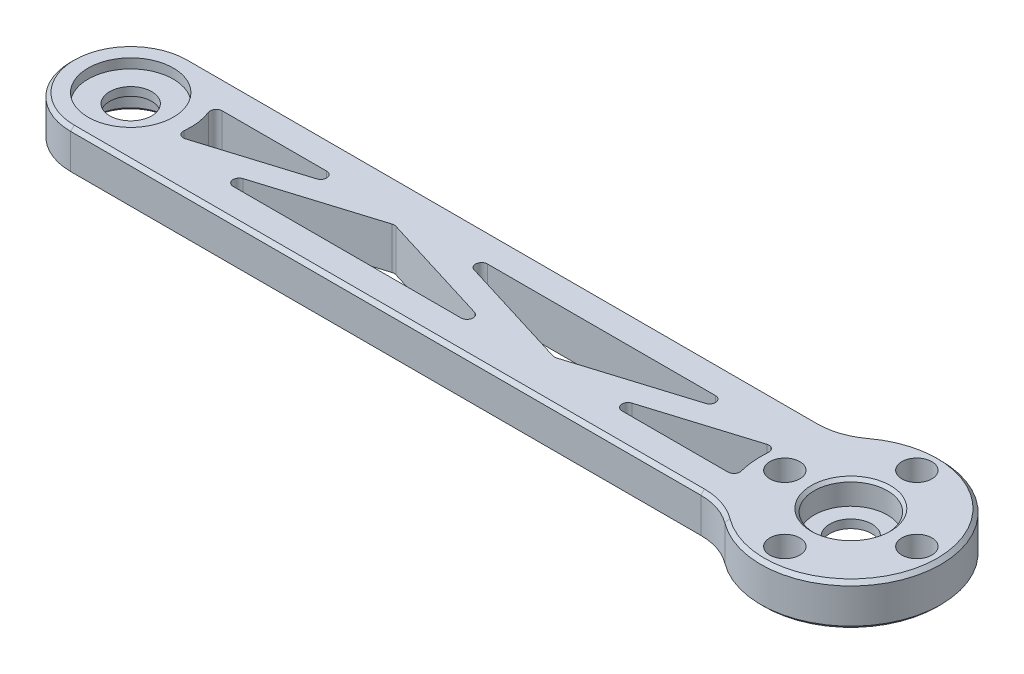
SolidWorks part; units mm, degrees
material "三聚氰胺甲醛树脂"
ref_plane "前视基准面" through (0, 0, 0) normal (0, 0, 1) x (1, 0, 0)
ref_plane "上视基准面" through (0, 0, 0) normal (0, 1, 0) x (1, 0, 0)
ref_plane "右视基准面" through (0, 0, 0) normal (1, 0, 0) x (0, 0, -1)
sketch "草图1" plane through (0, 0, 0) normal (0, 1, 0) x (1, 0, 0)
  line L0 (-120, 10) -> (-11.1803, 10)
  line L1 (-120, -10) -> (-11.1803, -10)
  line L2 (-104.5583, -5) -> (-53.3228, -5)
  line L3 (-111.3397, 5) -> (-85.722, 5)
  line L4 (-111.3397, -5) -> (-78.9405, 5) construction
  line L5 (-78.9405, 5) -> (-46.5413, -5) construction
  line L6 (-46.5413, -5) -> (-14.1421, 5) construction
  line L7 (-110.3438, -2.5995) -> (-85.722, 5)
  line L8 (-104.5583, -5) -> (-78.9405, 2.9069)
  line L9 (-78.9405, 2.9069) -> (-53.3228, -5)
  line L10 (-72.1591, 5) -> (-46.5413, -2.9069)
  line L11 (-46.5413, -2.9069) -> (-20.9236, 5)
  line L12 (-39.7599, -5) -> (-14.7515, 2.7188)
  line L13 (-72.1591, 5) -> (-20.9236, 5)
  line L14 (-39.7599, -5) -> (-14.1421, -5)
  circle A0 centre (0, 0) radius 11 construction
  circle A1 centre (-11, 0) radius 2.5
  circle A2 centre (0, 11) radius 2.5
  circle A3 centre (11, 0) radius 2.5
  circle A4 centre (0, -11) radius 2.5
  arc A7 (-14.7515, 2.7188) -> (-14.1421, -5) centre (0, 0) ccw
  arc A9 (-120, 10) -> (-120, -10) centre (-120, 0) ccw
  arc A10 (-11.1803, -10) -> (-11.1803, 10) centre (0, 0) ccw
  circle A11 centre (0, 0) radius 15 construction
  arc A12 (-110.3438, -2.5995) -> (-111.3397, 5) centre (-120, 0) ccw
  circle A13 centre (-120, 0) radius 10 construction
  point P14 (0, 0)
  dimension "D1" = 22
  dimension "D2" = 5
  dimension "D5" = 30
  dimension "D7" = 20
  dimension "D8" = 120
  dimension "D9" = 5
  dimension "D10" = 5
  dimension "D11" = 2
  dimension "D12" = 2
  dimension "D13" = 2
  dimension "D14" = 2
  dimension "D15" = 2
  dimension "D16" = 2
extrude "凸台-拉伸1" add sketch "草图1" along normal blind 7
fillet "圆角1" radius 1 3 edges at (-85.722, 3.5, -5) (-110.3438, 3.5, 2.5995) (-111.3397, 3.5, -5)
fillet "圆角2" radius 1 3 edges at (-53.3228, 3.5, 5) (-78.9405, 3.5, -2.9069) (-104.5583, 3.5, 5)
fillet "圆角3" radius 1 3 edges at (-20.9236, 3.5, -5) (-46.5413, 3.5, 2.9069) (-72.1591, 3.5, -5)
fillet "圆角4" radius 1 3 edges at (-39.7599, 3.5, 5) (-14.1421, 3.5, 5) (-14.7515, 3.5, -2.7188)
fillet "圆角5" radius 10 2 edges at (-11.1803, 3.5, 10) (-11.1803, 3.5, -10)
ref_plane "基准面1" through (0, 1.2, 0) normal (0, -1, 0) x (-1, 0, 0)
sketch "草图2" plane through (0, 0, 0) normal (0, -1, 0) x (-1, 0, 0)
  circle A0 centre (0, 0) radius 7.1
  dimension "D1" = 14.2
extrude "切除-拉伸1" cut sketch "草图2" against normal blind 1.6
sketch "草图3" plane through (0, 0, 0) normal (0, -1, 0) x (-1, 0, 0)
  circle A0 centre (120, 0) radius 6.1
  dimension "D1" = 12.2
extrude "切除-拉伸2" cut sketch "草图3" against normal blind 4
sketch "草图4" plane through (0, 7, 0) normal (0, 1, 0) x (1, 0, 0)
  circle A0 centre (0, 0) radius 6.1
  dimension "D1" = 12.2
extrude "切除-拉伸4" cut sketch "草图4" against normal blind 4 contours A0
sketch "草图5" plane through (0, 7, 0) normal (0, 1, 0) x (1, 0, 0)
  circle A0 centre (-120, 0) radius 7.1
  dimension "D1" = 14.2
extrude "切除-拉伸5" cut sketch "草图5" against normal blind 1.6
sketch "草图6" plane through (0, 3, 0) normal (0, 1, 0) x (1, 0, 0)
  circle A0 centre (0, 0) radius 3.5
  circle A1 centre (-120, 0) radius 3.5
  dimension "D1" = 7
  dimension "D2" = 7
extrude "切除-拉伸6" cut sketch "草图6" against normal mid plane 10
chamfer "倒角1" distance 0.6 angle 45 12 edges at (-130, 0, 0) (-67.5, 0, 10) (-67.5, 0, -10) (-11.8377, 0, 10.5132) (-11.8377, 0, -10.5132) (15, 0, 0) (-130, 7, 0) (-67.5, 7, 10) (-67.5, 7, -10) (-11.8377, 7, 10.5132) (-11.8377, 7, -10.5132) (15, 7, 0)
chamfer "倒角2" distance 0.5 angle 45 2 edges at (0, 7, 6.1) (-120, 0, -6.1)
